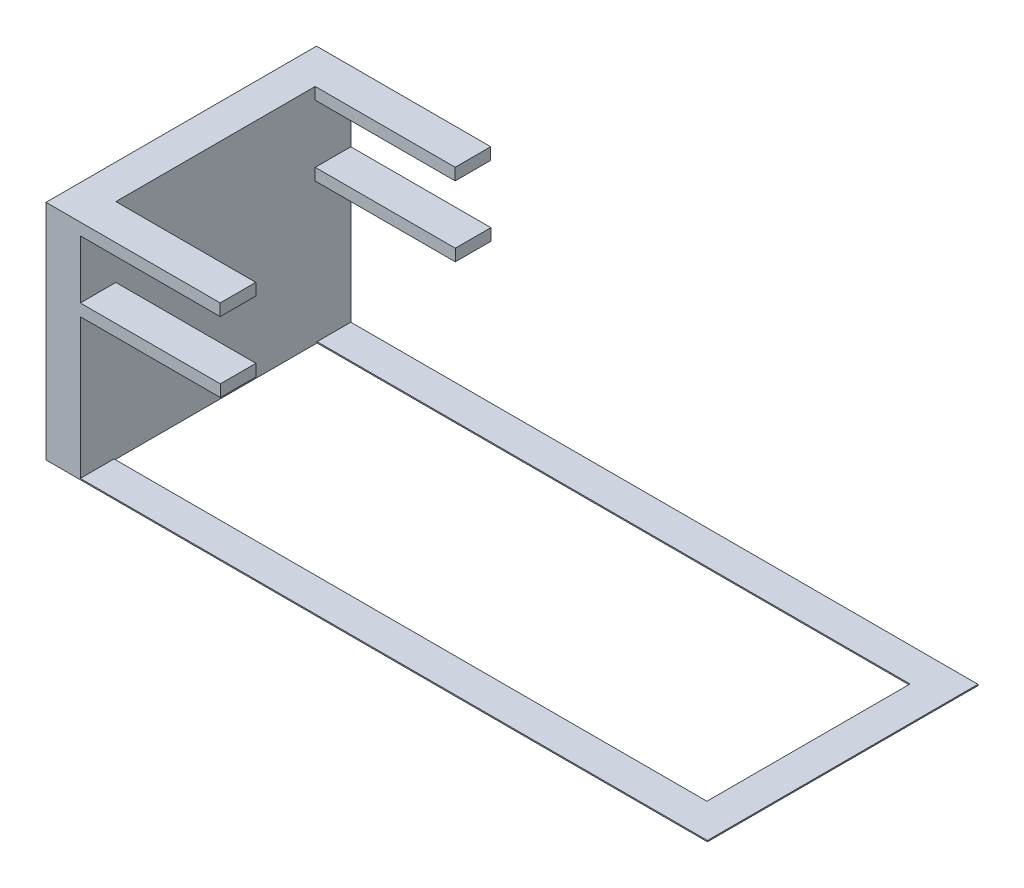
SolidWorks part; units mm, degrees
ref_plane "Front Plane" through (0, 0, 0) normal (0, 0, 1) x (1, 0, 0)
ref_plane "Top Plane" through (0, 0, 0) normal (0, 1, 0) x (1, 0, 0)
ref_plane "Right Plane" through (0, 0, 0) normal (1, 0, 0) x (0, 0, -1)
sketch "Sketch1" plane through (0, 0, 0) normal (0, 1, 0) x (1, 0, 0)
  line L1 (-708.4162, 289.7392) -> (708.4162, 289.7392)
  line L2 (-708.4162, 289.7392) -> (-708.4162, -289.7392)
  line L3 (-708.4162, -289.7392) -> (708.4162, -289.7392)
  line L4 (708.4162, 289.7392) -> (708.4162, -289.7392)
  line L5 (-708.4162, 289.7392) -> (708.4162, -289.7392) construction
  line L6 (-708.4162, -289.7392) -> (708.4162, 289.7392) construction
  line L7 (635, -217.4999) -> (-635, -217.4999)
  line L8 (635, -217.4999) -> (635, 217.4999)
  line L9 (635, 217.4999) -> (-635, 217.4999)
  line L10 (-635, -217.4999) -> (-635, 217.4999)
  line L11 (635, -217.4999) -> (-635, 217.4999) construction
  line L12 (635, 217.4999) -> (-635, -217.4999) construction
  point P0 (0, 0)
  point P6 (0, 0)
  point P11 (-555.271, 190.901)
  point P12 (-708.4162, 289.7392)
  dimension "D1" = 1270
  dimension "D2" = 434.9999
extrude "Boss-Extrude1" add sketch "Sketch1" along normal blind 2.54
sketch "Sketch2" plane through (0, 0, 0) normal (0, -1, 0) x (1, 0, 0)
  line L0 (708.4162, -289.7392) -> (-708.4162, -289.7392) construction
  line L1 (-708.4162, 289.7392) -> (-635, 289.7392)
  line L2 (-708.4162, 289.7392) -> (-708.4162, -289.7392)
  line L3 (-708.4162, -289.7392) -> (-635, -289.7392)
  line L4 (-635, 289.7392) -> (-635, -289.7392)
extrude "Boss-Extrude2" add sketch "Sketch2" against normal blind 327.9394 contours L4 L3 L2 L1
sketch "Sketch3" plane through (-635, 0, 0) normal (1, 0, 0) x (0, 0, -1)
  line L0 (0, 327.9394) -> (0, 21.9018) construction
  line L1 (-289.7392, 327.9394) -> (-213.5392, 327.9394)
  line L2 (-289.7392, 327.9394) -> (-289.7392, 302.5394)
  line L3 (-289.7392, 302.5394) -> (-213.5392, 302.5394)
  line L4 (-213.5392, 327.9394) -> (-213.5392, 302.5394)
  line L5 (-289.7392, 327.9394) -> (289.7392, 327.9394) construction
  line L6 (213.5392, 327.9394) -> (213.5392, 302.5394)
  line L7 (289.7392, 302.5394) -> (213.5392, 302.5394)
  line L8 (289.7392, 327.9394) -> (289.7392, 302.5394)
  line L9 (289.7392, 327.9394) -> (213.5392, 327.9394)
  dimension "D1" = 25.4
  dimension "D2" = 76.2
extrude "Boss-Extrude3" add sketch "Sketch3" along normal blind 299.9994
sketch "Sketch4" plane through (0, 327.9394, 0) normal (0, 1, 0) x (1, 0, 0)
  line L1 (-708.4162, 289.7392) -> (-635, 289.7392)
  line L2 (-708.4162, 289.7392) -> (-708.4162, -289.7392)
  line L3 (-708.4162, -289.7392) -> (-635, -289.7392)
  line L4 (-635, 289.7392) -> (-635, -289.7392)
extrude "Boss-Extrude4" add sketch "Sketch4" along normal blind 150
sketch "Sketch5" plane through (-635, 0, 0) normal (1, 0, 0) x (0, 0, -1)
  line L0 (0, 477.9394) -> (0, 0) construction
  line L1 (-289.7392, 477.9394) -> (-213.5392, 477.9394)
  line L2 (-289.7392, 477.9394) -> (-289.7392, 452.5394)
  line L3 (-289.7392, 452.5394) -> (-213.5392, 452.5394)
  line L4 (-213.5392, 477.9394) -> (-213.5392, 452.5394)
  line L5 (-289.7392, 477.9394) -> (289.7392, 477.9394) construction
  line L6 (213.5392, 477.9394) -> (213.5392, 452.5394)
  line L7 (289.7392, 452.5394) -> (213.5392, 452.5394)
  line L8 (289.7392, 477.9394) -> (289.7392, 452.5394)
  line L9 (289.7392, 477.9394) -> (213.5392, 477.9394)
  dimension "D1" = 25.4
extrude "Boss-Extrude5" add sketch "Sketch5" along normal blind 299.72
